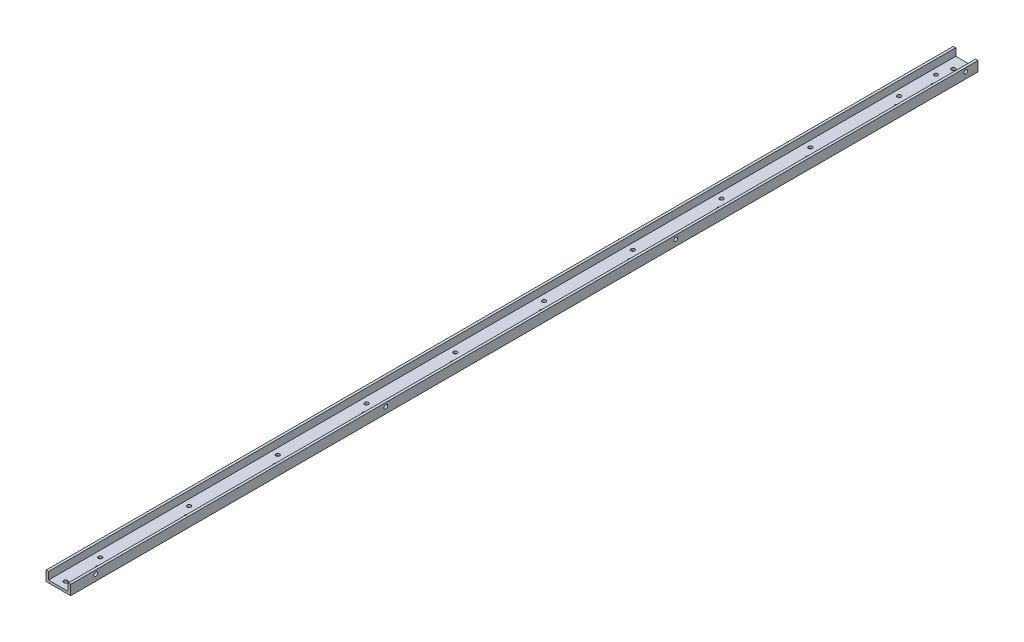
SolidWorks part; units mm, degrees
ref_plane "Front Plane" through (0, 0, 0) normal (0, 0, 1) x (1, 0, 0)
ref_plane "Top Plane" through (0, 0, 0) normal (0, 1, 0) x (1, 0, 0)
ref_plane "Right Plane" through (0, 0, 0) normal (1, 0, 0) x (0, 0, -1)
sketch "Sketch1" plane through (0, 0, 0) normal (0, 0, 1) x (1, 0, 0)
  line L0 (3.175, 3.175) -> (3.175, 12.7)
  line L1 (0, 0) -> (31.75, 0)
  line L2 (0, 0) -> (0, 12.7)
  line L4 (31.75, 0) -> (31.75, 12.7)
  line L5 (3.175, 3.175) -> (28.575, 3.175)
  line L6 (28.575, 3.175) -> (28.575, 12.7)
  line L7 (0, 12.7) -> (3.175, 12.7)
  line L8 (31.75, 12.7) -> (28.575, 12.7)
  dimension "D1" = 31.75
  dimension "D2" = 12.7
  dimension "D3" = 3.175
extrude "Boss-Extrude1" add sketch "Sketch1" along normal blind 1168.4
sketch "Sketch3" plane through (0, 3.175, 0) normal (0, 1, 0) x (1, 0, 0)
  line L0 (11.1125, -1109.6625) -> (11.1125, -1122.3625) construction
  line L1 (11.1125, -1122.3625) -> (20.6375, -1122.3625) construction
  line L2 (20.6375, -1122.3625) -> (11.1125, -1109.6625) construction
  line L3 (20.6375, -1122.3625) -> (20.6375, -1168.4) construction
  line L4 (28.575, -1168.4) -> (3.175, -1168.4) construction
  circle A1 centre (11.1125, -1109.6625) radius 2.413
  circle A3 centre (20.6375, -1122.3625) radius 2.413
  dimension "D1" = 9.525
  dimension "D2" = 12.7
  dimension "D3" = 46.0375
extrude "Cut-Extrude1" cut sketch "Sketch3" against normal up to next
sketch "Sketch4" plane through (0, 3.175, 0) normal (0, 1, 0) x (1, 0, 0)
  line L0 (15.875, -1168.4) -> (15.875, -1158.875) construction
  line L1 (28.575, -1168.4) -> (3.175, -1168.4) construction
  circle A0 centre (15.875, -1158.875) radius 2.413
  dimension "D2" = 4.826
  dimension "D1" = 9.525
extrude "Cut-Extrude2" cut sketch "Sketch4" against normal up to next
pattern_linear "LPattern1" count 10 spacing 114.3 along (0, 0, -1) of "Cut-Extrude1"
sketch "Sketch5" plane through (31.75, 0, 0) normal (1, 0, 0) x (0, 0, -1)
  circle A0 centre (-389.255, 7.9375) radius 2.413 construction
  circle A1 centre (-389.255, 7.9375) radius 2.413
  circle A2 centre (-15.875, 7.9375) radius 2.413 construction
  circle A3 centre (-15.875, 7.9375) radius 2.413
  circle A4 centre (-762.635, 7.9375) radius 2.413 construction
  circle A5 centre (-762.635, 7.9375) radius 2.413
  circle A6 centre (-1136.015, 7.9375) radius 2.413 construction
  circle A7 centre (-1136.015, 7.9375) radius 2.413
extrude "Cut-Extrude3" cut sketch "Sketch5" against normal up to next
sketch "Sketch6" plane through (0, 0, 0) normal (0, -1, 0) x (1, 0, 0)
  circle A0 centre (11.1125, 33.3375) radius 2.413 construction
  circle A1 centre (11.1125, 33.3375) radius 2.413
  circle A2 centre (20.6375, 46.0375) radius 2.413 construction
  circle A3 centre (20.6375, 46.0375) radius 2.413
extrude "Cut-Extrude4" cut sketch "Sketch6" against normal up to next
sketch "Sketch7" plane through (0, 3.175, 0) normal (0, 1, 0) x (1, 0, 0)
  line L0 (15.875, 0) -> (15.875, -15.875) construction
  line L1 (28.575, 0) -> (3.175, 0) construction
  circle A0 centre (15.875, -15.875) radius 2.413
  dimension "D2" = 4.826
  dimension "D1" = 15.875
extrude "Cut-Extrude5" cut sketch "Sketch7" against normal up to next
